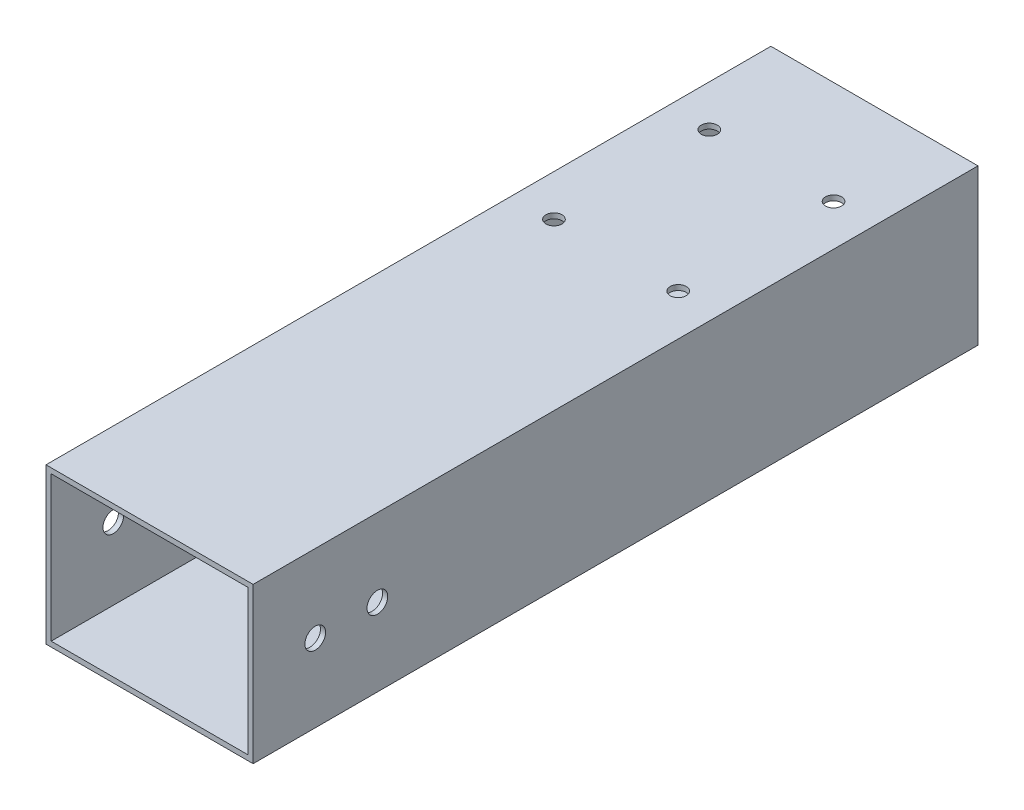
SolidWorks part; units mm, degrees
material "AISI 1015 钢，冷拔 (SS)"
ref_plane "前视基准面" through (0, 0, 0) normal (0, 0, 1) x (1, 0, 0)
ref_plane "上视基准面" through (0, 0, 0) normal (0, 1, 0) x (1, 0, 0)
ref_plane "右视基准面" through (0, 0, 0) normal (1, 0, 0) x (0, 0, -1)
other "Configuration Table"
sketch "草图1" plane through (0, 0, 0) normal (0, 0, 1) x (1, 0, 0)
  line L1 (0, 0) -> (40, 0)
  line L2 (0, 0) -> (0, 30)
  line L3 (0, 30) -> (40, 30)
  line L4 (40, 0) -> (40, 30)
  line L5 (1, 1) -> (39, 1)
  line L6 (1, 1) -> (1, 29)
  line L7 (1, 29) -> (39, 29)
  line L8 (39, 1) -> (39, 29)
  dimension "D1" = 40
  dimension "D2" = 30
  dimension "D3" = 1
  dimension "D4" = 1
  dimension "D5" = 1
  dimension "D6" = 1
extrude "凸台-拉伸1" add sketch "草图1" along normal blind 140
sketch "草图2" plane through (0, 0, 0) normal (1, 0, 0) x (0, 0, -1)
  line L0 (-70, 83.174) -> (-70, -57.7734) construction
  line L1 (-140, 30) -> (0, 30) construction
  line L2 (-234.5233, 15) -> (4.3455, 15) construction
  line L3 (0, 0) -> (0, 30) construction
  line L4 (-140, 0) -> (-140, 30) construction
  circle A0 centre (-116, 15) radius 2
  circle A1 centre (-128, 15) radius 2
  point P2 (-70, 30)
  point P7 (0, 15)
  dimension "D1" = 4
  dimension "D2" = 12
  dimension "D3" = 12
extrude "切除-拉伸1" cut sketch "草图2" along normal through all
sketch "草图3" plane through (0, 0, 0) normal (0, 1, 0) x (1, 0, 0)
  line L0 (20, 7.4176) -> (20, -220.6816) construction
  line L1 (-71.6968, -34.9) -> (105.9098, -34.9) construction
  circle A0 centre (8, -19.9) radius 1.55
  circle A1 centre (32, -19.9) radius 1.55
  circle A2 centre (32, -49.9) radius 1.55
  circle A3 centre (8, -49.9) radius 1.55
  dimension "D1" = 3.1
  dimension "D2" = 20
  dimension "D3" = 24
  dimension "D4" = 19.9
  dimension "D5" = 30
extrude "切除-拉伸2" cut sketch "草图3" along normal through all
